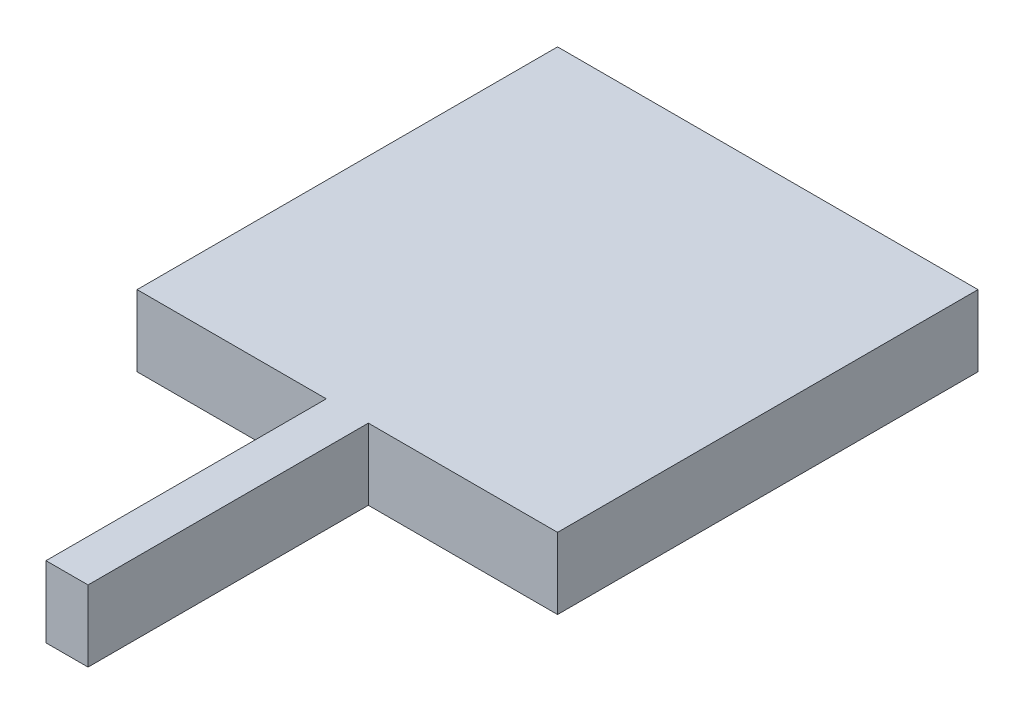
SolidWorks part; units mm, degrees
ref_plane "Front Plane" through (0, 0, 0) normal (0, 0, 1) x (1, 0, 0)
ref_plane "Top Plane" through (0, 0, 0) normal (0, 1, 0) x (1, 0, 0)
ref_plane "Right Plane" through (0, 0, 0) normal (1, 0, 0) x (0, 0, -1)
sketch "Sketch1" plane through (0, 0, 0) normal (0, 1, 0) x (1, 0, 0)
  line L0 (16.5, 0) -> (30, 0)
  line L1 (0, 0) -> (30, 0)
  line L2 (0, 0) -> (0, 30)
  line L3 (0, 30) -> (30, 30)
  line L4 (30, 0) -> (30, 30)
  line L5 (13.5, 0) -> (16.5, 0)
  line L6 (13.5, 0) -> (13.5, -20)
  line L7 (13.5, -20) -> (16.5, -20)
  line L8 (16.5, 0) -> (16.5, -20)
  line L9 (0, 0) -> (13.5, 0)
  dimension "D1" = 30
  dimension "D2" = 30
  dimension "D3" = 20
  dimension "D4" = 3
extrude "Boss-Extrude1" add sketch "Sketch1" along normal blind 5.08 contours L0 L4 L3 L2 L1 | L8 L1 L6 L7
